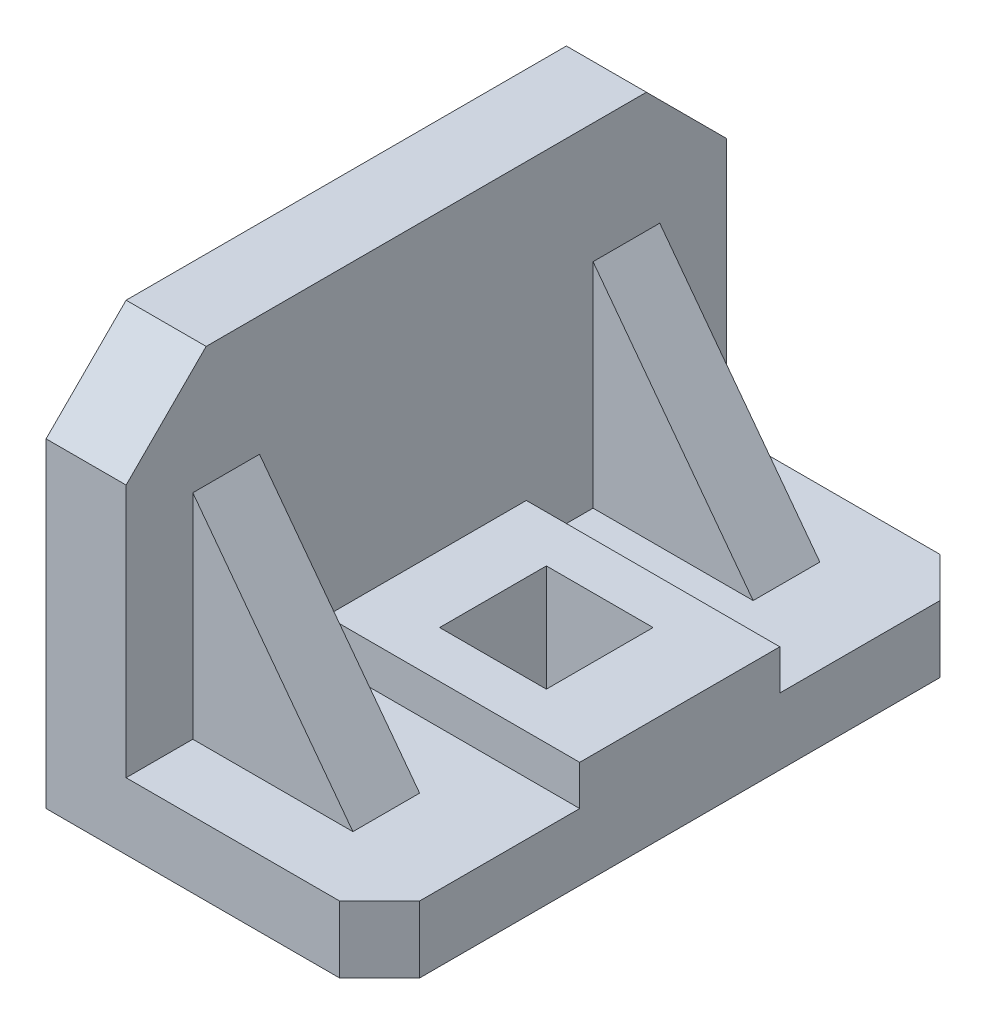
SolidWorks part; units mm, degrees
ref_plane "Ön Düzlem" through (0, 0, 0) normal (0, 0, 1) x (1, 0, 0)
ref_plane "Üst Düzlem" through (0, 0, 0) normal (0, 1, 0) x (1, 0, 0)
ref_plane "Sağ Düzlem" through (0, 0, 0) normal (1, 0, 0) x (0, 0, -1)
sketch "Çizim1" plane through (0, 0, 0) normal (0, 0, 1) x (1, 0, 0)
  line L1 (0, 1524) -> (304.8, 1524)
  line L2 (0, 1524) -> (0, 0)
  line L4 (304.8, 1524) -> (304.8, 406.4)
  line L5 (304.8, 406.4) -> (1270, 406.4)
  line L7 (0, 0) -> (1270, 0)
  line L8 (1270, 406.4) -> (1270, 0)
  dimension "D1" = 1524
  dimension "D2" = 1270
  dimension "D3" = 304.8
  dimension "D4" = 406.4
extrude "Yükseklik-Ekstrüzyon1" add sketch "Çizim1" along normal blind 2286
sketch "Çizim3" plane through (1270, 0, 0) normal (1, 0, 0) x (0, 0, -1)
  line L0 (-2286, 406.4) -> (0, 406.4) construction
  line L1 (-2286, 406.4) -> (-1524, 406.4)
  line L2 (-2286, 406.4) -> (-2286, 254)
  line L3 (-2286, 254) -> (-1524, 254)
  line L4 (-1524, 406.4) -> (-1524, 254)
  line L5 (-762, 406.4) -> (0, 406.4)
  line L6 (-762, 406.4) -> (-762, 254)
  line L7 (-762, 254) -> (0, 254)
  line L8 (0, 406.4) -> (0, 254)
  line L9 (0, 0) -> (0, 406.4) construction
  dimension "D1" = 152.4
  dimension "D2" = 152.4
  dimension "D3" = 762
  dimension "D4" = 762
extrude "Kes-Ekstrüzyon4" cut sketch "Çizim3" against normal blind 965.2
sketch "Çizim9" plane through (304.8, 0, 0) normal (1, 0, 0) x (0, 0, -1)
  line L0 (-1981.2, 1524) -> (-2286, 1219.2)
  line L1 (-1981.2, 1524) -> (-2252.9982, 1795.7982)
  line L2 (-2286, 1219.2) -> (-2557.7982, 1490.9982)
  line L3 (-2252.9982, 1795.7982) -> (-2557.7982, 1490.9982)
  line L4 (-2286, 1524) -> (0, 1524) construction
  line L5 (-2286, 254) -> (-2286, 1524) construction
  line L6 (-304.8, 1524) -> (0, 1219.2)
  line L7 (-304.8, 1524) -> (-39.3972, 1789.4028)
  line L8 (0, 1219.2) -> (265.4028, 1484.6028)
  line L9 (-39.3972, 1789.4028) -> (265.4028, 1484.6028)
  line L10 (0, 254) -> (0, 1524) construction
  dimension "D1" = 304.8
  dimension "D2" = 304.8
  dimension "D3" = 304.8
  dimension "D4" = 304.8
extrude "Kes-Ekstrüzyon5" cut sketch "Çizim9" against normal blind 304.8 contours L0 L1 L3 L2 | L6 L7 L9 L8
sketch "Çizim10" plane through (0, 254, 0) normal (0, 1, 0) x (1, 0, 0)
  line L0 (1117.6, 0) -> (1270, -152.4)
  line L1 (1117.6, 0) -> (1325.822, 208.222)
  line L2 (1270, -152.4) -> (1478.222, 55.822)
  line L3 (1325.822, 208.222) -> (1478.222, 55.822)
  line L4 (304.8, 0) -> (1270, 0) construction
  line L5 (1270, -762) -> (1270, 0) construction
  line L12 (1270, -2133.6) -> (1117.6, -2286)
  line L13 (1270, -2133.6) -> (1466.1362, -2329.7362)
  line L14 (1117.6, -2286) -> (1313.7362, -2482.1362)
  line L15 (1466.1362, -2329.7362) -> (1313.7362, -2482.1362)
  line L16 (1270, -2286) -> (1270, -1524) construction
  line L17 (304.8, -2286) -> (1270, -2286) construction
  dimension "D1" = 152.4
  dimension "D2" = 152.4
  dimension "D3" = 152.4
  dimension "D4" = 152.4
extrude "Kes-Ekstrüzyon6" cut sketch "Çizim10" against normal blind 304.8
sketch "Çizim11" plane through (0, 406.4, 0) normal (0, 1, 0) x (1, 0, 0)
  line L0 (304.8, -1524) -> (1270, -1524) construction
  line L1 (558.8, -939.8) -> (965.2, -939.8)
  line L2 (558.8, -939.8) -> (558.8, -1346.2)
  line L3 (558.8, -1346.2) -> (965.2, -1346.2)
  line L4 (965.2, -939.8) -> (965.2, -1346.2)
  line L5 (304.8, -1981.2) -> (304.8, -304.8) construction
  dimension "D1" = 177.8
  dimension "D2" = 406.4
  dimension "D3" = 254
  dimension "D4" = 406.4
extrude "Kes-Ekstrüzyon7" cut sketch "Çizim11" against normal blind 406.4
sketch "Çizim12" plane through (304.8, 0, 0) normal (1, 0, 0) x (0, 0, -1)
  line L0 (-2133.6, 254) -> (-1524, 254) construction
  line L1 (-2032, 1066.8) -> (-1778, 1066.8)
  line L2 (-2032, 1066.8) -> (-2032, 254)
  line L3 (-2032, 254) -> (-1778, 254)
  line L4 (-1778, 1066.8) -> (-1778, 254)
  line L5 (-762, 254) -> (0, 254) construction
  line L6 (-508, 1066.8) -> (-254, 1066.8)
  line L7 (-508, 1066.8) -> (-508, 254)
  line L8 (-508, 254) -> (-254, 254)
  line L9 (-254, 1066.8) -> (-254, 254)
  line L10 (-2286, 254) -> (-2286, 1219.2) construction
  line L11 (0, 254) -> (0, 1219.2) construction
  dimension "D1" = 254
  dimension "D2" = 254
  dimension "D3" = 812.8
  dimension "D4" = 812.8
  dimension "D5" = 254
  dimension "D6" = 254
extrude "Yükseklik-Ekstrüzyon3" add sketch "Çizim12" along normal blind 609.6
sketch "Çizim14" plane through (0, 0, 2032) normal (0, 0, 1) x (1, 0, 0)
  line L0 (304.8, 1066.8) -> (914.4, 254)
  line L1 (304.8, 1066.8) -> (769.1321, 1415.0491)
  line L2 (914.4, 254) -> (1378.7321, 602.2491)
  line L3 (769.1321, 1415.0491) -> (1378.7321, 602.2491)
extrude "Kes-Ekstrüzyon10" cut sketch "Çizim14" against normal blind 254
sketch "Çizim15" plane through (0, 0, 254) normal (0, 0, -1) x (-1, 0, 0)
  line L0 (-304.8, 1066.8) -> (-914.4, 254)
  line L1 (-304.8, 1066.8) -> (-869.918, 1490.6385)
  line L2 (-914.4, 254) -> (-1479.518, 677.8385)
  line L3 (-869.918, 1490.6385) -> (-1479.518, 677.8385)
  line L4 (-914.4, 1066.8) -> (-304.8, 1066.8) construction
  line L5 (-304.8, 254) -> (-304.8, 1066.8) construction
  line L6 (-304.8, 254) -> (-1117.6, 254) construction
  line L7 (-304.8, 254) -> (-1270, 254) construction
extrude "Kes-Ekstrüzyon11" cut sketch "Çizim15" against normal blind 254
